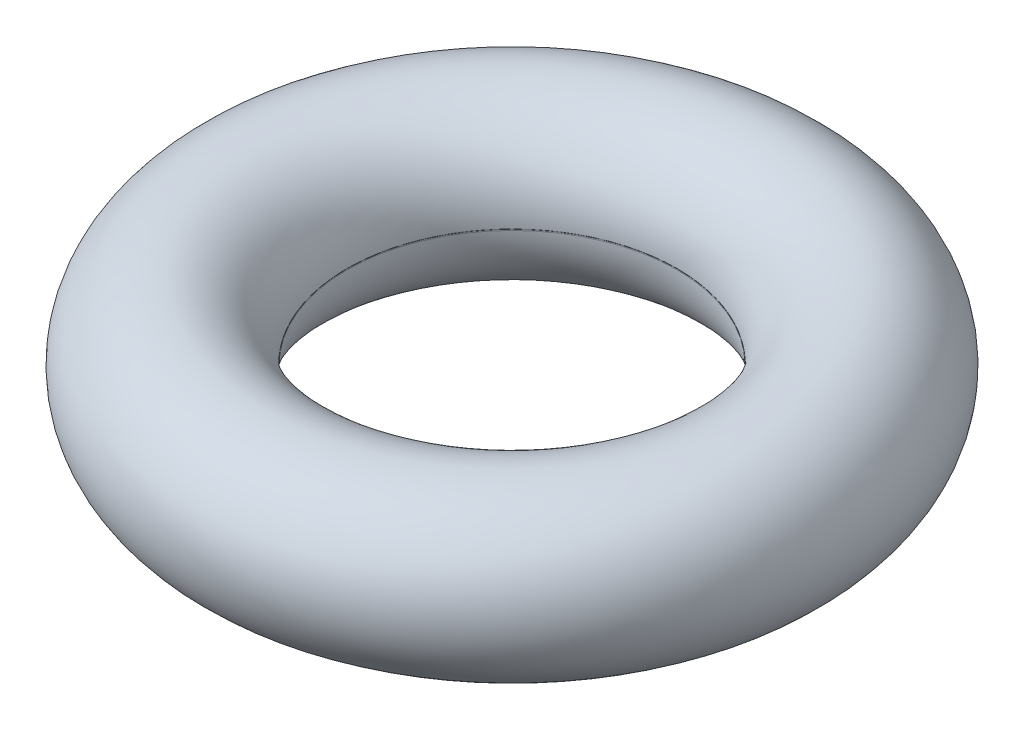
SolidWorks part; units mm, degrees
material "Borracha de silicone"
ref_plane "Plano frontal" through (0, 0, 0) normal (0, 0, 1) x (1, 0, 0)
ref_plane "Plano superior" through (0, 0, 0) normal (0, 1, 0) x (1, 0, 0)
ref_plane "Plano direito" through (0, 0, 0) normal (1, 0, 0) x (0, 0, -1)
sketch "Esboço1" plane through (0, 0, 0) normal (0, 0, 1) x (1, 0, 0)
  line L0 (0, 0) -> (2.25, 0) construction
  line L1 (0, 0) -> (0, 1.8052) construction
  circle A0 centre (2.25, 0) radius 0.75
  dimension "D2" = 1.5
  dimension "D1" = 2.25
revolve "Revolução1" add sketch "Esboço1" angle 360 about L1
sketch "Esboço2" plane through (0, 0, 0) normal (0, 1, 0) x (1, 0, 0)
  circle A0 centre (0, 0) radius 1.505
  circle A1 centre (0, 0) radius 1.5
  dimension "D1" = 3.01
  dimension "D2" = 3
extrude "Ressalto-extrusão1" add sketch "Esboço2" along normal blind 0.01 separate body contours A0 A1 | A1
